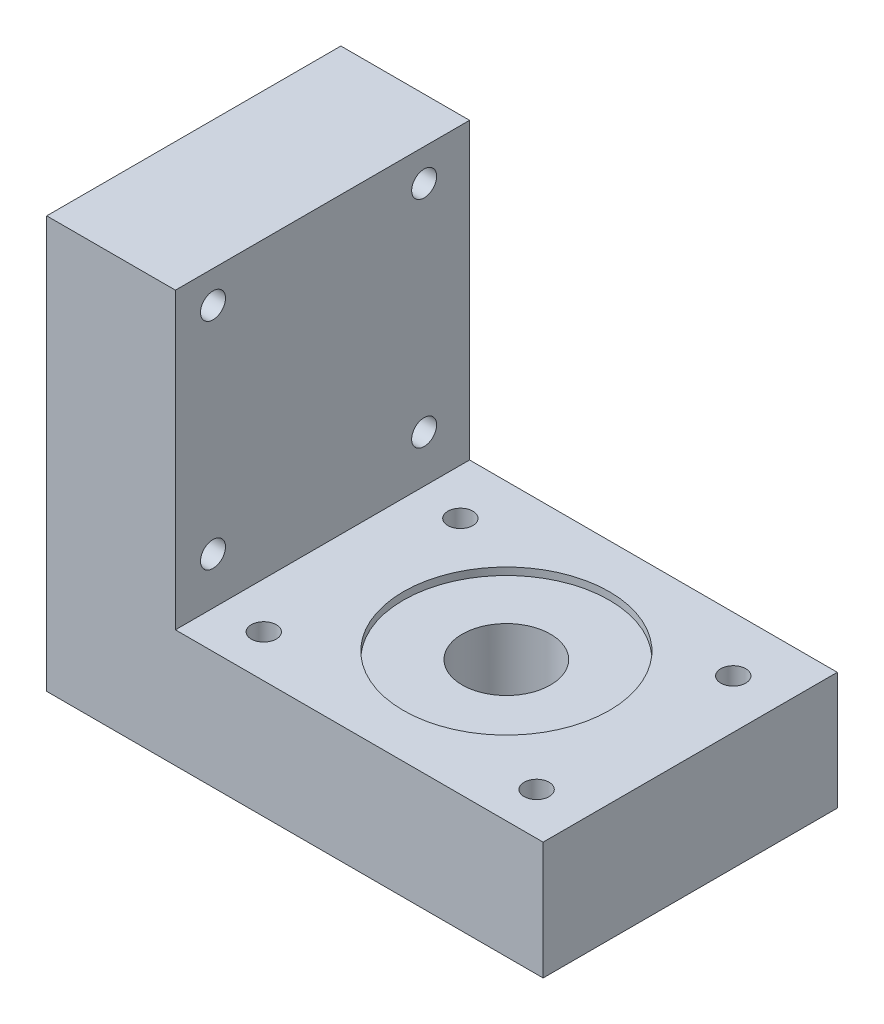
SolidWorks part; units mm, degrees
ref_plane "Front Plane" through (0, 0, 0) normal (0, 0, 1) x (1, 0, 0)
ref_plane "Top Plane" through (0, 0, 0) normal (0, 1, 0) x (1, 0, 0)
ref_plane "Right Plane" through (0, 0, 0) normal (1, 0, 0) x (0, 0, -1)
sketch "Sketch2" plane through (0, 0, 0) normal (0, 0, 1) x (1, 0, 0)
  line L0 (0, 56000) -> (0, 0)
  line L1 (0, 0) -> (67500, 0)
  line L2 (67500, 0) -> (67500, 16000)
  line L3 (67500, 16000) -> (17500, 16000)
  line L4 (17500, 16000) -> (17500, 56000)
  line L5 (17500, 56000) -> (0, 56000)
  dimension "D1" = 17500
  dimension "D2" = 16000
  dimension "D3" = 67500
  dimension "D4" = 56000
extrude "Boss-Extrude1" add sketch "Sketch2" along normal blind 40000
sketch "Sketch3" plane through (0, 16000, 0) normal (0, 1, 0) x (1, 0, 0)
  line L0 (23750, 0) -> (23750, -7500) construction
  line L2 (17500, 0) -> (30000, 0) construction
  circle A0 centre (42500, -20000) radius 6000
  circle A1 centre (23750, -7500) radius 1700
  circle A2 centre (60851.2734, -7500) radius 1700
  circle A3 centre (60851.2734, -34236.0811) radius 1700
  circle A4 centre (23750, -34236.0811) radius 1700
  dimension "D1" = 12000
  dimension "D3" = 3400
  dimension "D2" = 7500
extrude "Cut-Extrude1" cut sketch "Sketch3" along direction (0, 1, 0) on the side against the normal up to next (16000 mm away)
sketch "Sketch4" plane through (17500, 0, 0) normal (1, 0, 0) x (0, 0, -1)
  circle A0 centre (-34887.5833, 51657.3946) radius 1700
  circle A1 centre (-6177.4046, 51657.3946) radius 1700
  circle A2 centre (-34887.5833, 22377.1581) radius 1700
  circle A3 centre (-6177.4046, 22377.1581) radius 1700
  dimension "D1" = 3400
extrude "Cut-Extrude2" cut sketch "Sketch4" along direction (1, 0, 0) on the side against the normal up to next (17500 mm away)
sketch "Sketch5" plane through (0, 16000, 0) normal (0, 1, 0) x (1, 0, 0)
  circle A0 centre (42500, -20000) radius 14000
  dimension "D1" = 28000
extrude "Cut-Extrude3" cut sketch "Sketch5" against normal blind 1000
equation "\"L1\"= 50mm"
equation "\"L2\"= 40mm"
equation "\"B1\"= 35mm"
equation "\"B2\"= 40mm"
equation "\"H1\"= 16mm"
equation "\"H2\"= 12.5mm"
equation "\"P\"= 300"
equation "\"E\"= 3500000"
equation "\"dmax\"= 4 * \"P\" * \"L1\" ^ 3 / ( \"E\" * \"B1\" * \"H1\" ^ 3 )"
